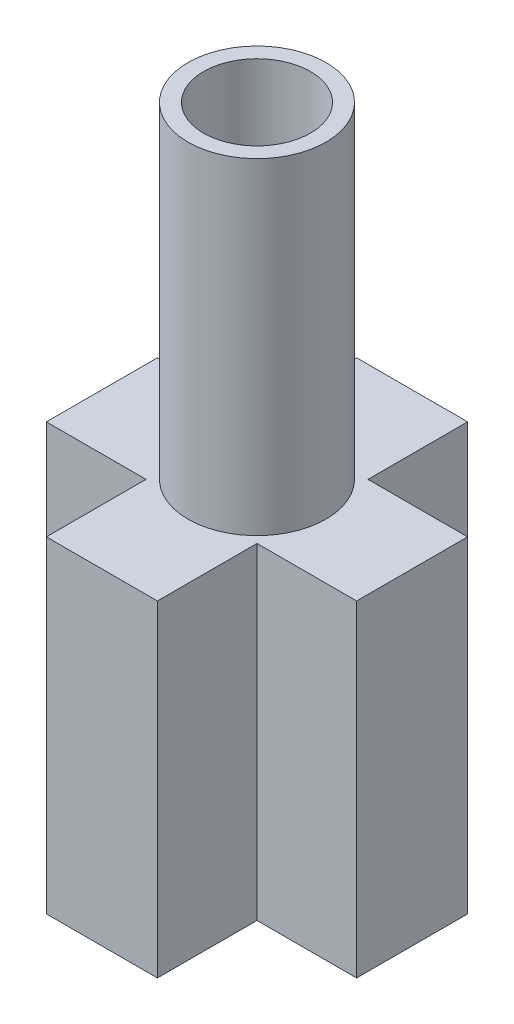
SolidWorks part; units mm, degrees
ref_plane "Front Plane" through (0, 0, 0) normal (0, 0, 1) x (1, 0, 0)
ref_plane "Top Plane" through (0, 0, 0) normal (0, 1, 0) x (1, 0, 0)
ref_plane "Right Plane" through (0, 0, 0) normal (1, 0, 0) x (0, 0, -1)
sketch "Sketch1" plane through (0, 0, 0) normal (0, 1, 0) x (1, 0, 0)
  line L0 (0.8636, 0.8636) -> (2.413, 0.8636)
  line L1 (-0.8636, 2.413) -> (0.8636, 2.413)
  line L2 (-0.8636, 2.413) -> (-0.8636, 0.8636)
  line L3 (-0.8636, -2.413) -> (0.8636, -2.413)
  line L4 (0.8636, 2.413) -> (0.8636, 0.8636)
  line L5 (-2.413, 0.8636) -> (0, 0) construction
  line L6 (2.413, -0.8636) -> (0, 0) construction
  line L7 (-2.413, -0.8636) -> (-0.8636, -0.8636)
  line L8 (-2.413, -0.8636) -> (-2.413, 0.8636)
  line L9 (-2.413, 0.8636) -> (-0.8636, 0.8636)
  line L10 (2.413, -0.8636) -> (2.413, 0.8636)
  line L11 (0, 0) -> (2.413, 0.8636) construction
  line L12 (-2.413, -0.8636) -> (0, 0) construction
  line L13 (0.8636, 2.413) -> (0, 0) construction
  line L14 (-0.8636, -0.8636) -> (-0.8636, -2.413)
  line L15 (0, 0) -> (-0.8636, 2.413) construction
  line L16 (-0.8636, -2.413) -> (0, 0) construction
  line L17 (0.8636, -0.8636) -> (0.8636, -2.413)
  line L19 (0.8636, -0.8636) -> (2.413, -0.8636)
  line L21 (0, 0) -> (0.8636, -2.413) construction
  point P0 (0, 0)
  point P6 (0, 0)
  dimension "D1" = 1.7272
extrude "Boss-Extrude1" add sketch "Sketch1" along normal blind 5.08
sketch "Sketch2" plane through (0, 5.08, 0) normal (0, 1, 0) x (1, 0, 0)
  circle A0 centre (0, 0) radius 1.0733
  circle A2 centre (0, 0) radius 0.8314
  dimension "D1" = 1.6628
  dimension "D2" = 2.1466
extrude "Boss-Extrude2" add sketch "Sketch2" along normal blind 5.08
sketch "Sketch4" plane through (0, 5.08, 0) normal (0, 1, 0) x (1, 0, 0)
  circle A0 centre (0, 0) radius 0.8314
extrude "Cut-Extrude1" cut sketch "Sketch4" against normal blind 3.81
